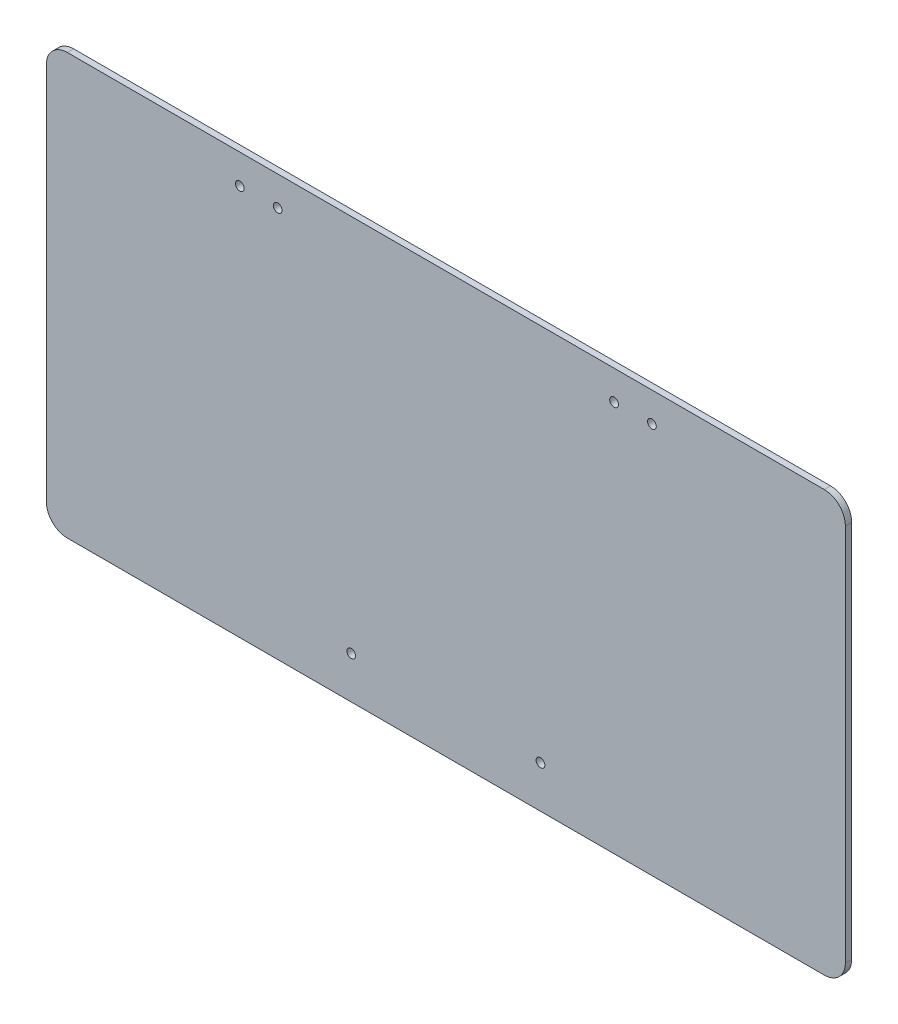
SolidWorks part; units mm, degrees
ref_plane "前视基准面" through (0, 0, 0) normal (0, 0, 1) x (1, 0, 0)
ref_plane "上视基准面" through (0, 0, 0) normal (0, 1, 0) x (1, 0, 0)
ref_plane "右视基准面" through (0, 0, 0) normal (1, 0, 0) x (0, 0, -1)
other "Configuration Table"
sketch "草图1" plane through (0, 0, 0) normal (0, 0, 1) x (1, 0, 0)
  line L1 (-190, 100) -> (190, 100)
  line L2 (-190, 100) -> (-190, -100)
  line L3 (-190, -100) -> (190, -100)
  line L4 (190, 100) -> (190, -100)
  line L5 (-190, 100) -> (190, -100) construction
  line L6 (-190, -100) -> (190, 100) construction
  point P0 (0, 0)
  dimension "D1" = 200
  dimension "D2" = 380
extrude "凸台-拉伸1" add sketch "草图1" along normal blind 3
sketch "草图2" plane through (0, 0, 3) normal (0, 0, 1) x (1, 0, 0)
  line L0 (0, 0) -> (0, 130.0137) construction
  line L1 (190, 100) -> (-190, 100) construction
  circle A0 centre (-98, 86) radius 2.075
  circle A1 centre (-80, 86) radius 2.075
  circle A2 centre (80, 86) radius 2.075
  circle A3 centre (98, 86) radius 2.075
  point P9 (0, 0)
  point P10 (0, 0)
  point P11 (0, 0)
  dimension "D1" = 18
  dimension "D4" = 4.15
  dimension "D2" = 14
  dimension "D3" = 160
extrude "切除-拉伸1" cut sketch "草图2" against normal through all
fillet "圆角1" radius 10 4 edges at (190, -100, 1.5) (-190, -100, 1.5) (190, 100, 1.5) (-190, 100, 1.5)
sketch "草图3" plane through (0, 0, 3) normal (0, 0, 1) x (1, 0, 0)
  line L0 (45, -80) -> (-45, -80) construction
  circle A0 centre (-45, -80) radius 2.075
  circle A1 centre (45, -80) radius 2.075
  point P4 (0, -80)
  point P5 (45, -85.1289)
  dimension "D1" = 4.15
  dimension "D2" = 90
  dimension "D3" = 80
extrude "切除-拉伸2" cut sketch "草图3" against normal blind 5
